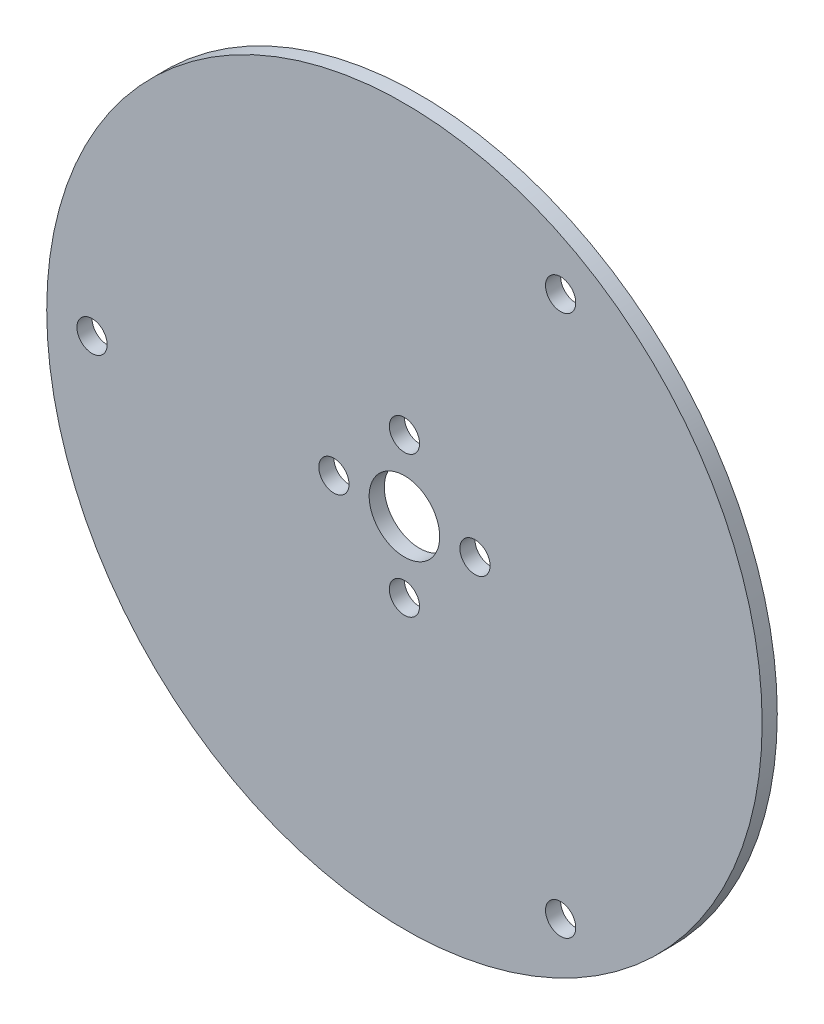
SolidWorks part; units mm, degrees
ref_plane "前视基准面" through (0, 0, 0) normal (0, 0, 1) x (1, 0, 0)
ref_plane "上视基准面" through (0, 0, 0) normal (0, 1, 0) x (1, 0, 0)
ref_plane "右视基准面" through (0, 0, 0) normal (1, 0, 0) x (0, 0, -1)
sketch "草图1" plane through (0, 0, 0) normal (0, 0, 1) x (1, 0, 0)
  circle A0 centre (0, 0) radius 35.5
extrude "凸台-拉伸1" add sketch "草图1" along normal blind 1.5
sketch "草图2" plane through (0, 0, 1.5) normal (0, 0, 1) x (1, 0, 0)
  circle A0 centre (0, 0) radius 3.5
extrude "切除-拉伸1" cut sketch "草图2" against normal blind 2
sketch "草图3" plane through (0, 0, 1.5) normal (0, 0, 1) x (1, 0, 0)
  circle A0 centre (0, 7) radius 1.5
  circle A1 centre (7, 0) radius 1.5
  circle A2 centre (0, -7) radius 1.5
  circle A3 centre (-7, 0) radius 1.5
  point P12 (0, 0)
  dimension "D1" = 4
extrude "切除-拉伸2" cut sketch "草图3" against normal blind 2
sketch "草图5" plane through (0, 0, 1.5) normal (0, 0, 1) x (1, 0, 0)
  circle A0 centre (-31, 0) radius 1.5
  circle A1 centre (15.5, 26.8468) radius 1.5
  circle A2 centre (15.5, -26.8468) radius 1.5
  point P10 (0, 0)
  dimension "D1" = 3
extrude "切除-拉伸3" cut sketch "草图5" against normal blind 2
